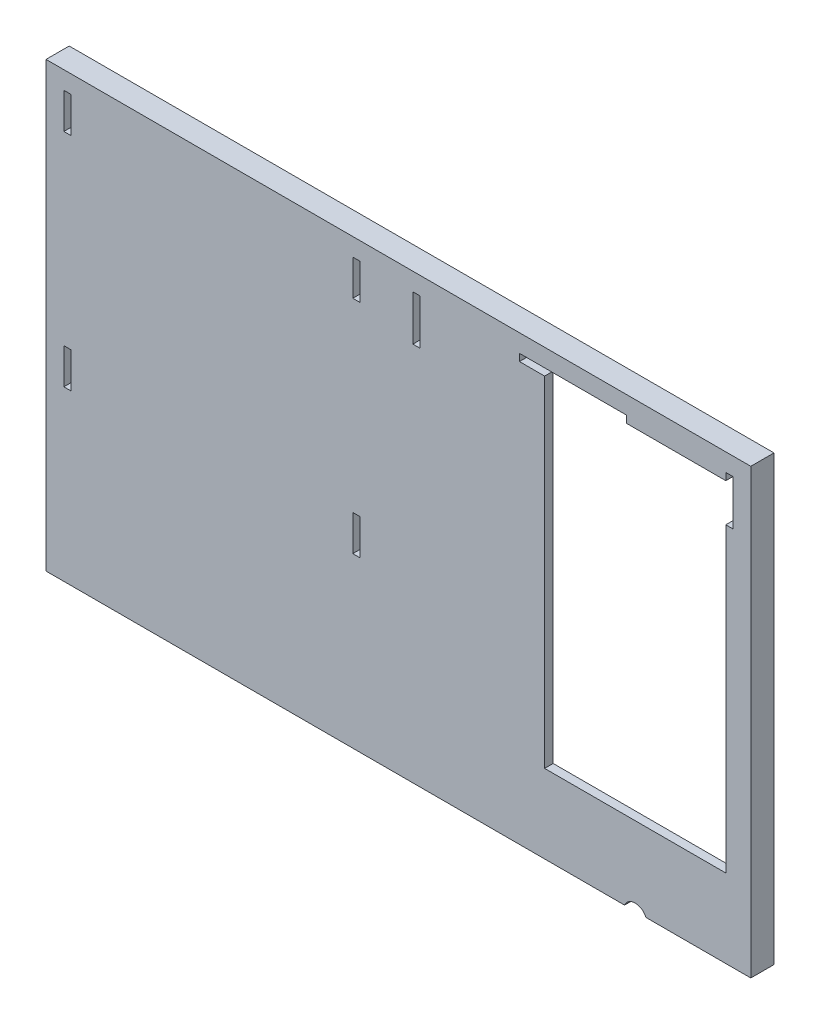
SolidWorks part; units mm, degrees
ref_plane "Front Plane" through (0, 0, 0) normal (0, 0, 1) x (1, 0, 0)
ref_plane "Top Plane" through (0, 0, 0) normal (0, 1, 0) x (1, 0, 0)
ref_plane "Right Plane" through (0, 0, 0) normal (1, 0, 0) x (0, 0, -1)
sketch "Sketch1" plane through (0, 0, 0) normal (0, 0, 1) x (1, 0, 0)
  line L1 (0, 0) -> (195.58, 0)
  line L2 (0, 0) -> (0, 244.475)
  line L3 (0, 244.475) -> (195.58, 244.475)
  line L4 (195.58, 0) -> (195.58, 244.475)
  dimension "D1" = 195.58
  dimension "D2" = 244.475
extrude "Boss-Extrude1" add sketch "Sketch1" along normal blind 2.4
sketch "Sketch2" plane through (0, 0, 2.4) normal (0, 0, 1) x (1, 0, 0)
  line L0 (195.58, 244.475) -> (197.58, 244.475) construction
  line L1 (195.58, 0) -> (0, 0)
  line L3 (196.9234, -2) -> (0, -2)
  line L4 (0, 0) -> (0, -2)
  line L5 (195.58, 244.475) -> (0, 244.475)
  line L7 (195.58, 246.475) -> (0, 246.475)
  line L8 (0, 244.475) -> (0, 246.475)
  line L9 (196.9234, -2) -> (197.58, -2)
  line L10 (195.58, 0) -> (195.58, 244.475)
  line L11 (195.58, 246.475) -> (197.58, 246.475)
  line L12 (197.58, -2) -> (197.58, 246.475)
  dimension "D1" = 2
extrude "Boss-Extrude2" add sketch "Sketch2" against normal offset from surface (4.5 mm away) 2.1 up to face at (97.79, 122.2375, 0) offset beyond the face yes
sketch "Sketch3" plane through (0, 0, -2.1) normal (0, 0, -1) x (-1, 0, 0)
  line L0 (-195.58, 244.475) -> (-195.58, 0) construction
  line L1 (0, -2) -> (-197.58, -2)
  line L2 (0, -2) -> (0, 3.9688)
  line L3 (0, 3.9688) -> (-195.58, 3.9688)
  line L5 (-197.58, 246.475) -> (0, 246.475)
  line L7 (-195.58, 240.5062) -> (0, 240.5062)
  line L8 (0, 246.475) -> (0, 240.5062)
  line L10 (-197.58, -2) -> (-197.58, 246.475)
  line L12 (-195.58, 3.9688) -> (-195.58, 240.5062)
  dimension "D1" = 236.5375
extrude "Boss-Extrude3" add sketch "Sketch3" along normal blind 2
sketch "Sketch4" plane through (0, 0, 2.4) normal (0, 0, 1) x (1, 0, 0)
  line L0 (7, 231.475) -> (7, 179.475) construction
  line L1 (5, 241.475) -> (7, 241.475)
  line L2 (5, 241.475) -> (5, 231.475)
  line L3 (5, 231.475) -> (7, 231.475)
  line L4 (7, 241.475) -> (7, 231.475)
  line L5 (5, 179.475) -> (7, 179.475)
  line L6 (5, 179.475) -> (5, 169.475)
  line L7 (5, 169.475) -> (7, 169.475)
  line L8 (7, 179.475) -> (7, 169.475)
  line L9 (197.58, 246.475) -> (0, 246.475) construction
  line L10 (0, 246.475) -> (0, -2) construction
  line L11 (7, 241.475) -> (46.5, 241.475) construction
  line L12 (46.5, 241.475) -> (46.5, 181.5011) construction
  line L13 (88, 169.475) -> (86, 169.475)
  line L14 (86, 179.475) -> (86, 169.475)
  line L15 (88, 179.475) -> (86, 179.475)
  line L16 (88, 179.475) -> (88, 169.475)
  line L17 (88, 231.475) -> (86, 231.475)
  line L18 (86, 241.475) -> (86, 231.475)
  line L19 (88, 241.475) -> (86, 241.475)
  line L20 (88, 241.475) -> (88, 231.475)
  dimension "D1" = 10
  dimension "D2" = 2
  dimension "D3" = 10
  dimension "D4" = 52
  dimension "D5" = 5
  dimension "D6" = 5
  dimension "D7" = 39.5
extrude "Cut-Extrude1" cut sketch "Sketch4" against normal up to surface (2.4 mm away) up to face at (97.79, 122.2375, 0)
sketch "Sketch5" plane through (0, 0, 2.4) normal (0, 0, 1) x (1, 0, 0)
  line L0 (162.7175, 239.475) -> (190.58, 239.475)
  line L1 (139.78, 239.475) -> (132.7175, 239.475)
  line L2 (139.78, 239.475) -> (139.78, 144.225)
  line L3 (139.78, 144.225) -> (190.58, 144.225)
  line L4 (190.58, 228.775) -> (190.58, 144.225)
  line L5 (102.855, 241.475) -> (104.855, 241.475)
  line L6 (102.855, 241.475) -> (102.855, 228.775)
  line L7 (102.855, 228.775) -> (104.855, 228.775)
  line L8 (104.855, 241.475) -> (104.855, 228.775)
  line L9 (132.7175, 241.475) -> (162.7175, 241.475)
  line L10 (132.7175, 241.475) -> (132.7175, 239.475)
  line L12 (162.7175, 241.475) -> (162.7175, 239.475)
  line L13 (190.58, 241.475) -> (192.58, 241.475)
  line L14 (190.58, 241.475) -> (190.58, 239.475)
  line L15 (190.58, 228.775) -> (192.58, 228.775)
  line L16 (192.58, 241.475) -> (192.58, 228.775)
  line L17 (104.855, 241.475) -> (132.7175, 241.475) construction
  line L18 (162.7175, 241.475) -> (190.58, 241.475) construction
  line L19 (197.58, -2) -> (197.58, 246.475) construction
  line L20 (197.58, 246.475) -> (0, 246.475) construction
  dimension "D1" = 50.8
  dimension "D2" = 95.25
  dimension "D3" = 34.925
  dimension "D4" = 30
  dimension "D5" = 2
  dimension "D6" = 5
  dimension "D7" = 5
  dimension "D8" = 12.7
  dimension "D9" = 85.725
extrude "Cut-Extrude2" cut sketch "Sketch5" against normal up to surface (2.4 mm away) up to face at (87, 236.475, 0)
sketch "Sketch6" plane through (0, 0, 2.4) normal (0, 0, 1) x (1, 0, 0)
  line L0 (168.43, 120.975) -> (193.83, 120.975) construction
  line L2 (165.18, 124.225) -> (165.18, 144.225) construction
  line L3 (139.78, 144.225) -> (190.58, 144.225) construction
  circle A0 centre (165.18, 120.975) radius 3.25
  circle A1 centre (165.18, 100.975) radius 3.25
  circle A2 centre (165.18, 80.975) radius 3.25
  circle A3 centre (165.18, 60.975) radius 3.25
  circle A4 centre (165.18, 40.975) radius 3.25
  dimension "D1" = 25.4
  dimension "D3" = 6.5
  dimension "D2" = 20
  dimension "D4" = 5
extrude "Cut-Extrude3" cut sketch "Sketch6" against normal through all
ref_plane "Plane1" through (0, 122.2375, 0) normal (0, 1, 0) x (1, 0, 0)
sketch "Sketch7" plane through (0, 122.2375, 0) normal (0, 1, 0) x (1, 0, 0)
  line L1 (-11.6031, 14.7276) -> (237.1029, 14.7276)
  line L2 (-11.6031, 14.7276) -> (-11.6031, -11.9502)
  line L3 (-11.6031, -11.9502) -> (237.1029, -11.9502)
  line L4 (237.1029, 14.7276) -> (237.1029, -11.9502)
extrude "Cut-Extrude4" cut sketch "Sketch7" against normal through all
